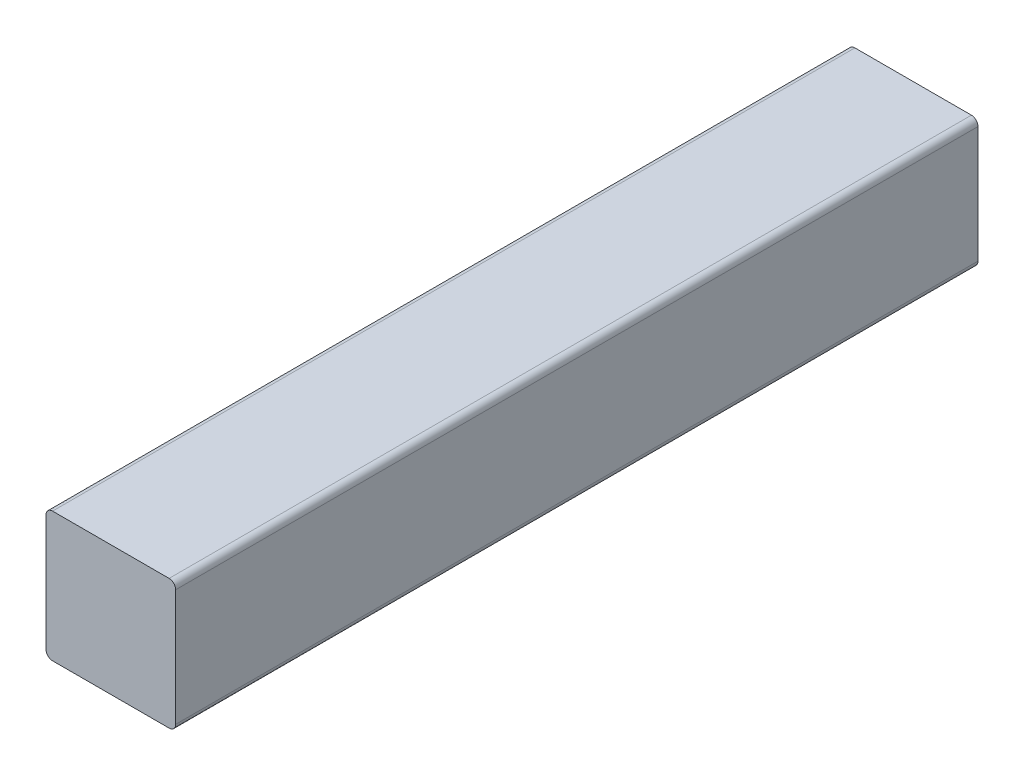
SolidWorks part; units mm, degrees
ref_plane "Front Plane" through (0, 0, 0) normal (0, 0, 1) x (1, 0, 0)
ref_plane "Top Plane" through (0, 0, 0) normal (0, 1, 0) x (1, 0, 0)
ref_plane "Right Plane" through (0, 0, 0) normal (1, 0, 0) x (0, 0, -1)
sketch "Sketch1" plane through (0, 0, 0) normal (0, 0, 1) x (1, 0, 0)
  line L1 (-10.033, 10.033) -> (10.033, 10.033)
  line L2 (-10.033, 10.033) -> (-10.033, -10.033)
  line L3 (-10.033, -10.033) -> (10.033, -10.033)
  line L4 (10.033, 10.033) -> (10.033, -10.033)
  line L5 (-10.033, 10.033) -> (10.033, -10.033) construction
  line L6 (-10.033, -10.033) -> (10.033, 10.033) construction
  point P0 (0, 0)
  dimension "D1" = 20.066
  dimension "D2" = 20.066
extrude "Boss-Extrude1" add sketch "Sketch1" along normal mid plane 124.1552
fillet "Fillet1" radius 1.016 4 edges at (-10.033, -10.033, 0) (10.033, -10.033, 0) (-10.033, 10.033, 0) (10.033, 10.033, 0)
